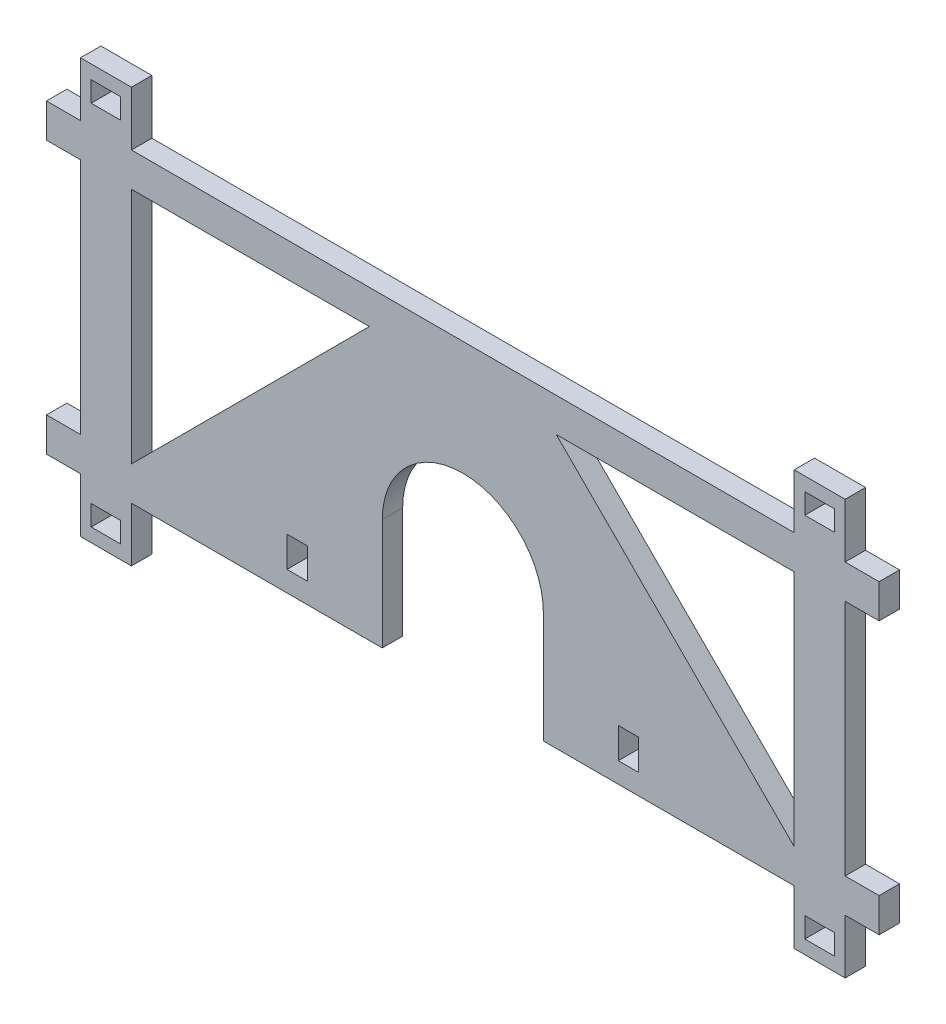
SolidWorks part; units mm, degrees
ref_plane "Front Plane" through (0, 0, 0) normal (0, 0, 1) x (1, 0, 0)
ref_plane "Top Plane" through (0, 0, 0) normal (0, 1, 0) x (1, 0, 0)
ref_plane "Right Plane" through (0, 0, 0) normal (1, 0, 0) x (0, 0, -1)
sketch "Sketch1" plane through (0, 0, 0) normal (0, 0, 1) x (1, 0, 0)
  line L0 (198.9667, 76.2) -> (198.9667, 67.7333)
  line L5 (198.9667, 67.7333) -> (190.5, 67.7333)
  line L6 (190.5, 0) -> (198.9667, 0)
  line L7 (198.9667, 0) -> (198.9667, 8.4667)
  line L8 (198.9667, 8.4667) -> (190.5, 8.4667)
  line L9 (-8.4667, 76.2) -> (-8.4667, 67.7333)
  line L10 (-8.4667, 67.7333) -> (0, 67.7333)
  line L11 (-8.4667, 76.2) -> (0, 76.2)
  line L12 (0, 0) -> (-8.4667, 0)
  line L13 (-8.4667, 0) -> (-8.4667, 8.4667)
  line L14 (-8.4667, 8.4667) -> (0, 8.4667)
  line L15 (0, 76.2) -> (0, 67.7333) construction
  line L16 (190.5, 76.2) -> (190.5, 67.7333) construction
  line L17 (190.5, 8.4667) -> (190.5, 0) construction
  line L18 (0, 8.4667) -> (0, 0) construction
  line L19 (198.9667, 76.2) -> (190.5, 76.2)
  line L20 (0, 67.7333) -> (0, 8.4667)
  line L21 (190.5, 67.7333) -> (190.5, 8.4667)
  line L22 (0, 0) -> (0, -13.5467)
  line L23 (0, -13.5467) -> (12.7, -13.5467)
  line L24 (12.7, -13.5467) -> (12.7, 0)
  line L25 (190.5, 0) -> (190.5, -13.5467)
  line L26 (190.5, -13.5467) -> (177.8, -13.5467)
  line L27 (177.8, -13.5467) -> (177.8, 0)
  line L28 (190.5, 76.2) -> (190.5, 89.7467)
  line L29 (190.5, 89.7467) -> (177.8, 89.7467)
  line L30 (177.8, 89.7467) -> (177.8, 76.2)
  line L31 (0, 76.2) -> (0, 89.7467)
  line L32 (0, 89.7467) -> (12.7, 89.7467)
  line L33 (12.7, 89.7467) -> (12.7, 76.2)
  line L34 (0, 76.2) -> (12.7, 76.2) construction
  line L35 (177.8, 76.2) -> (190.5, 76.2) construction
  line L36 (177.8, 0) -> (190.5, 0) construction
  line L37 (0, 0) -> (12.7, 0) construction
  line L38 (12.7, 76.2) -> (177.8, 76.2)
  line L39 (12.7, 0) -> (177.8, 0)
  dimension "D1" = 190.5
  dimension "D2" = 76.2
  dimension "D3" = 8.4667
  dimension "D4" = 8.4667
  dimension "D5" = 13.5467
  dimension "D6" = 12.7
extrude "Boss-Extrude1" add sketch "Sketch1" along normal blind 5.08
sketch "Sketch2" plane through (0, 0, 5.08) normal (0, 0, 1) x (1, 0, 0)
  line L0 (95.25, 0) -> (95.25, 47.752) construction
  line L1 (12.7, 0) -> (177.8, 0) construction
  line L2 (95.25, 0) -> (115.316, 0)
  line L3 (115.316, 0) -> (115.316, 27.686)
  line L5 (75.184, 27.686) -> (75.184, 0)
  line L6 (95.25, 0) -> (75.184, 0)
  line L7 (75.184, 0) -> (115.316, 0) construction
  arc A0 (115.316, 27.686) -> (75.184, 27.686) centre (95.25, 27.686) ccw
  dimension "D1" = 47.752
  dimension "D2" = 20.066
extrude "Cut-Extrude2" cut sketch "Sketch2" against normal through all
sketch "Sketch3" plane through (0, 0, 5.08) normal (0, 0, 1) x (1, 0, 0)
  line L0 (177.8, 76.2) -> (190.5, 76.2) construction
  line L1 (177.8, 0) -> (190.5, 0) construction
  line L2 (0, 0) -> (12.7, 0) construction
  line L3 (0, 76.2) -> (12.7, 76.2) construction
  line L4 (6.35, 76.2) -> (6.35, 81.28) construction
  line L5 (184.15, 76.2) -> (184.15, 81.28) construction
  line L6 (184.15, 0) -> (184.15, -5.08) construction
  line L7 (6.35, 0) -> (6.35, -5.08) construction
  line L8 (6.35, 81.28) -> (10.033, 81.28)
  line L9 (10.033, 81.28) -> (10.033, 86.36)
  line L10 (10.033, 86.36) -> (2.667, 86.36)
  line L11 (2.667, 86.36) -> (2.667, 81.28)
  line L12 (2.667, 81.28) -> (6.35, 81.28)
  line L13 (184.15, 81.28) -> (187.833, 81.28)
  line L14 (187.833, 81.28) -> (187.833, 86.36)
  line L15 (187.833, 86.36) -> (180.467, 86.36)
  line L16 (180.467, 86.36) -> (180.467, 81.28)
  line L17 (180.467, 81.28) -> (184.15, 81.28)
  line L18 (184.15, -5.08) -> (187.833, -5.08)
  line L19 (187.833, -5.08) -> (187.833, -10.16)
  line L20 (187.833, -10.16) -> (180.467, -10.16)
  line L21 (180.467, -10.16) -> (180.467, -5.08)
  line L22 (180.467, -5.08) -> (184.15, -5.08)
  line L23 (6.35, -5.08) -> (10.033, -5.08)
  line L24 (10.033, -5.08) -> (10.033, -10.16)
  line L25 (10.033, -10.16) -> (2.667, -10.16)
  line L26 (2.667, -10.16) -> (2.667, -5.08)
  line L27 (2.667, -5.08) -> (6.35, -5.08)
  dimension "D1" = 5.08
  dimension "D2" = 5.08
  dimension "D3" = 3.683
extrude "Cut-Extrude4" cut sketch "Sketch3" against normal through all
sketch "Sketch4" plane through (0, 0, 5.08) normal (0, 0, 1) x (1, 0, 0)
  line L0 (12.7, 0) -> (53.975, 0) construction
  line L1 (12.7, 0) -> (75.184, 0) construction
  line L2 (53.975, 0) -> (95.25, 0) construction
  line L3 (95.25, 0) -> (136.525, 0) construction
  line L4 (115.316, 0) -> (177.8, 0) construction
  line L5 (136.525, 0) -> (177.8, 0) construction
  line L6 (53.975, 0) -> (53.975, 5.08) construction
  line L7 (136.525, 0) -> (136.525, 5.08) construction
  line L8 (136.525, 5.08) -> (139.065, 5.08)
  line L9 (139.065, 5.08) -> (139.065, 12.7)
  line L10 (139.065, 12.7) -> (133.985, 12.7)
  line L11 (133.985, 12.7) -> (133.985, 5.08)
  line L12 (133.985, 5.08) -> (136.525, 5.08)
  line L13 (53.975, 5.08) -> (56.515, 5.08)
  line L14 (56.515, 5.08) -> (56.515, 12.7)
  line L15 (56.515, 12.7) -> (51.435, 12.7)
  line L16 (51.435, 12.7) -> (51.435, 5.08)
  line L17 (51.435, 5.08) -> (53.975, 5.08)
  dimension "D1" = 5.08
  dimension "D2" = 2.54
  dimension "D3" = 7.62
extrude "Cut-Extrude5" cut sketch "Sketch4" against normal through all
sketch "Sketch5" plane through (0, 0, 5.08) normal (0, 0, 1) x (1, 0, 0)
  line L0 (0, 67.7333) -> (12.7, 67.7333) construction
  line L1 (12.7, 67.7333) -> (12.7, 76.2) construction
  line L2 (0, 8.4667) -> (12.7, 8.4667) construction
  line L3 (12.7, 8.4667) -> (12.7, 0) construction
  line L4 (12.7, 67.7333) -> (12.7, 8.4667)
  line L5 (12.7, 8.4667) -> (71.9667, 67.7333)
  line L6 (71.9667, 67.7333) -> (12.7, 67.7333)
extrude "Cut-Extrude6" cut sketch "Sketch5" against normal through all contours L6 L4 L5
ref_plane "Plane1" through (95.25, 0, 0) normal (1, 0, 0) x (0, 0, -1)
mirror "Mirror1" about plane through (95.25, 0, 0) normal (1, 0, 0) of "Cut-Extrude6"
equation "\"FoamCore\" = \".2\""
equation "\"MDF\" = \".2\""
equation "\"GMaterial\"= \".2\""
equation "\"PVCMountDiameter\" = \"0.5in\""
equation "\"PVCMountDistanceToEdge\" = \"0.5\""
equation "\"PVCThickness\" = \"0.13in\""
equation "\"PVCDiameter\" = 1.5in"
equation "\"BaseWidth\" = \"8in\""
equation "\"BaseLength\" = \"10in\""
equation "\"BallDiameter\" = \"38mm\""
equation "\"BaseGap\" = \"4in\""
equation "\"FunnelTopDiameter\" = \"8in\""
equation "\"FunnelTopDepth\" = \"0.5in\""
equation "\"BallGap\" = \"0.1in\""
equation "\"FunnelLength\" = 3in"
equation "\"FunnelMaterial\" = 0.1in"
equation "\"FunnelLowerDiameter\" = 1.9in"
equation "\"FunnelDepth\" = 1.5in"
equation "\"FunnelBendLength\" = 2*pi*\"FunnelLowerDiameter\"/2*135"
equation "\"AmmoFeederLength\" = 1.5in + 76mm"
equation "\"WheelThickness\" = 0.5in"
equation "\"LauncherWheelDiameter\" = 76mm"
equation "\"MotorFrontLength\" = 0.95in"
equation "\"MotorBodyTotalLength\" = 2.03in"
equation "\"MotorFrontDiameter\" = 1.5in"
equation "\"MotorLowerDriveshaftDiameter\" = 0.46in"
equation "\"MotorLowerDriveshaftThickness\" = 0.25in"
equation "\"MotorFullDriveshaftLength\" = 0.78in"
equation "\"MotorDriveshaftDiameter\" = 0.23in"
equation "\"MotorDriveshaftFlatThickness\" = 0.2in"
equation "\"MotorRearDiameter\" = 31.9mm"
equation "\"MotorDriveshaftBottomToTop\" = 31.1mm"
equation "\"MotorFlatDriveshaftLength\" = 11.7mm"
equation "\"MotorDistanceBetweenLowerandTopHoles\" = 0.5in"
equation "\"MotorMountsDistanceFromEdge\" = 0.06in"
equation "\"MotorScrewMountDiameter\" = 0.1in"
equation "\"MotorScrewMountDepth\" = 0.13in"
equation "\"HBRidgeScrewHoleDeep\" = 0.18in"
equation "\"MotorMountWidth\" = \"1.61in\""
equation "\"MotorMountLength\" = \"1.58in\""
equation "\"MotorMountToEdgeGap\" = \"3.3mm\""
equation "\"MotorMountToInsideEdgeGap\" = \"6.5mm\""
equation "\"MotorMountToMountWidthGap\" = \"25.8mm\""
equation "\"MotorMountToMountLengthGap\" = \"20.5mm\""
equation "\"MotorMountMaterialThickness\" = 1.6mm"
equation "\"MotorMountBaseScrewholeDiameter\" = 3.8mm"
equation "\"MotorMountBaseDistancebetweenHoles\" = 0.8in"
equation "\"MotorMountHeight\" = 1.85in"
equation "\"HBridgeWidth\" = 2.25in"
equation "\"HBridgeLength\" = 1.40in"
equation "\"UnoWidth\" = 3.13in"
equation "\"UnoLength\" = 3.06in"
equation "\"BatteryWidth\" = 1.15in"
equation "\"BatteryLength\" = 3.86in"
equation "\"ScrewDiameter\" = 2.7mm"
equation "\"MotorMountFaceScrewtoBase\" = 0.46in"
equation "\"MotorMountFaceDistanceBetweenScrews\" = 0.95in"
equation "\"MotorMountFaceMiddletoEdge\" = 0.16in"
equation "\"MotorMountFaceBottomtoEdge\" = 0.42in"
equation "\"MotorMountCenterholeHeight\" = 1.04in"
equation "\"MotorMountCenterholetoEdge\" = 0.25in"
equation "\"MovingWheelDiameter\" = 76mm"
equation "\"MovingWheelThickness\" = 0.5in"
equation "\"BraceLength\" = 1in"
equation "\"BraceVerticalOffset\" = 3.5in"
equation "\"BraceHorizontalOffset\" = 2.5in"
equation "\"BaseToBaseDistance\" = 3in"
equation "\"PVCOutsideDiameter\" = \"PVCDiameter\" + 2*\"PVCThickness\""
equation "\"D1@Sketch1\"=\"BraceVerticalOffset\"*2+\"BraceLength\"/2"
equation "\"D2@Sketch1\"=\"BaseToBaseDistance\""
equation "\"D3@Sketch1\"=\"BraceLength\"/3"
equation "\"D4@Sketch1\"=\"BraceLength\"/3"
equation "\"D5@Sketch1\"=\"MDF\"+\"BraceLength\"/3"
equation "\"D6@Sketch1\"=\"BraceLength\"/2"
equation "\"D1@Boss-Extrude1\"=\"MDF\""
equation "\"D1@Sketch2\"=\"MotorMountHeight\"+0.03"
equation "\"D2@Sketch2\"=\"MotorMountLength\"/2"
equation "\"D1@Sketch3\"=\"MDF\""
equation "\"D2@Sketch3\"=\"MDF\""
equation "\"AmmoFeederCutoffLength\"= \"MovingWheelDiameter\""
equation "\"Distancebetweenwalls\" = 6in"
equation "\"Slidewidth\" = 0.3in"
equation "\"Slidelength\" = 0.8in"
equation "\"D3@Sketch3\"=\"Slidewidth\"/2-0.005"
equation "\"Bottomtofloor\" = 0.53in"
equation "\"tabdistance\" = 0.2in"
equation "\"tabwidth\" = 0.3in"
equation "\"D1@Sketch4\"=\"tabdistance\""
equation "\"D2@Sketch4\"=\"MDF\"/2"
equation "\"D3@Sketch4\"=\"tabwidth\""
